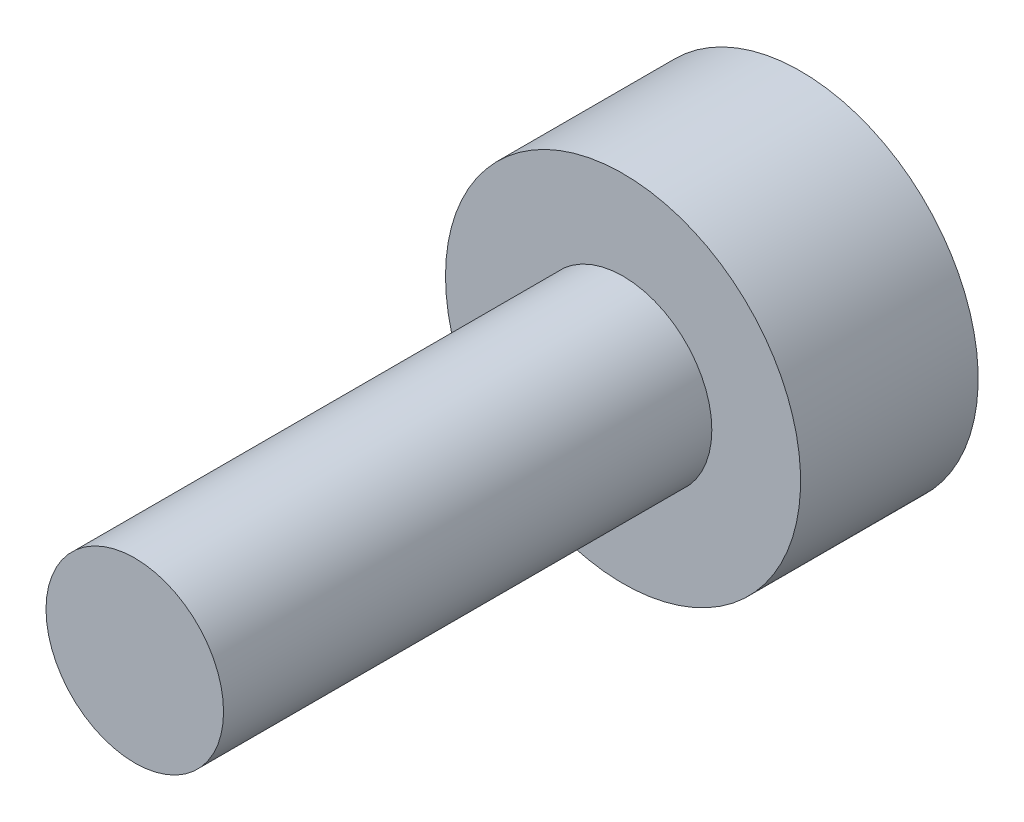
SolidWorks part; units mm, degrees
ref_plane "前视基准面" through (0, 0, 0) normal (0, 0, 1) x (1, 0, 0)
ref_plane "上视基准面" through (0, 0, 0) normal (0, 1, 0) x (1, 0, 0)
ref_plane "右视基准面" through (0, 0, 0) normal (1, 0, 0) x (0, 0, -1)
sketch "草图1" plane through (0, 0, 0) normal (0, 0, 1) x (1, 0, 0)
  circle A0 centre (0, 0) radius 1
extrude "凸台-拉伸1" add sketch "草图1" along normal blind 5.5
sketch "草图2" plane through (0, 0, 0) normal (0, 0, -1) x (-1, 0, 0)
  circle A0 centre (0, 0) radius 2
extrude "凸台-拉伸2" add sketch "草图2" along normal blind 2
sketch "草图3" plane through (0, 0, -2) normal (0, 0, -1) x (-1, 0, 0)
  line L1 (1, 0) -> (0.5, 0.866)
  line L2 (0.5, 0.866) -> (-0.5, 0.866)
  line L3 (-0.5, 0.866) -> (-1, 0)
  line L4 (-1, 0) -> (-0.5, -0.866)
  line L5 (-0.5, -0.866) -> (0.5, -0.866)
  line L6 (0.5, -0.866) -> (1, 0)
  circle A0 centre (0, 0) radius 1 construction
extrude "切除-拉伸1" cut sketch "草图3" against normal blind 1
